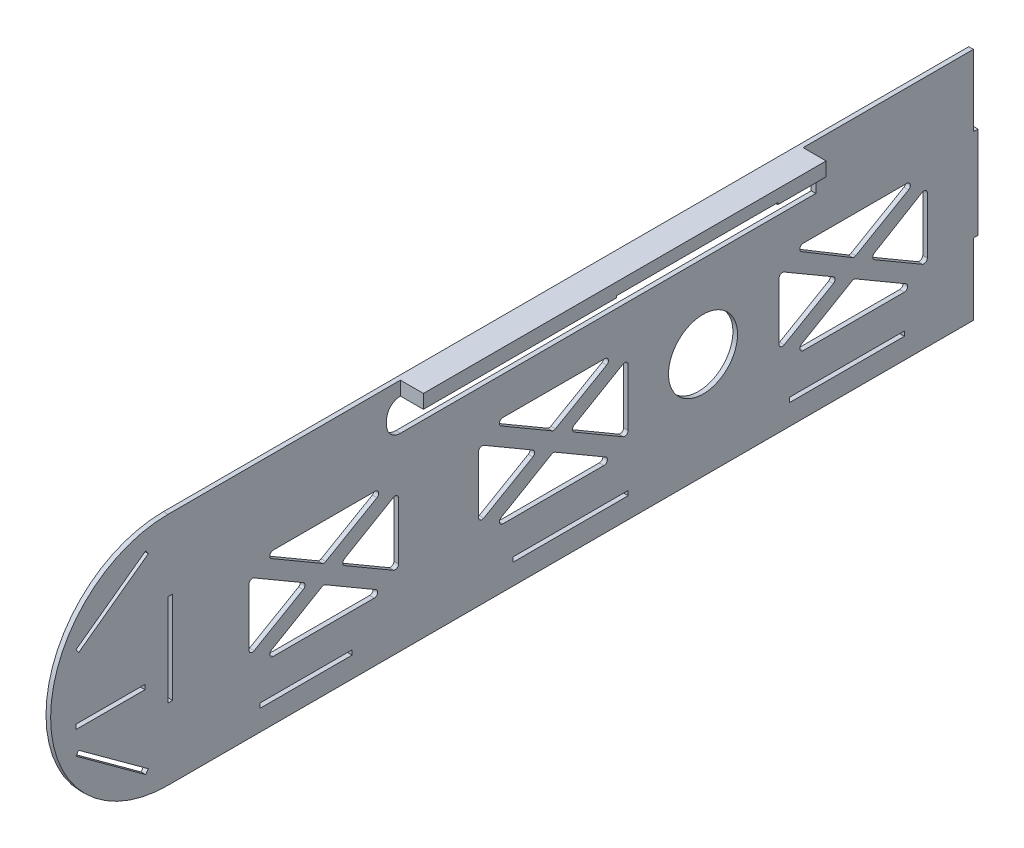
SolidWorks part; units mm, degrees
ref_plane "前视基准面" through (0, 0, 0) normal (0, 0, 1) x (1, 0, 0)
ref_plane "上视基准面" through (0, 0, 0) normal (0, 1, 0) x (1, 0, 0)
ref_plane "右视基准面" through (0, 0, 0) normal (1, 0, 0) x (0, 0, -1)
sketch "草图1" plane through (0, 0, 0) normal (1, 0, 0) x (0, 0, -1)
  line L0 (95, 39) -> (95, 37)
  line L1 (0, 51) -> (139, 51)
  line L2 (0, 51) -> (0, -51)
  line L3 (0, -51) -> (350, -51)
  line L4 (350, 51) -> (350, -51)
  line L5 (145, 51) -> (281.5, 51)
  line L6 (101, 31) -> (275.5, 31)
  line L7 (281.5, 39) -> (281.5, 36)
  line L8 (337.5, 51) -> (350, 51)
  line L10 (-40, -10) -> (-10, -10)
  line L11 (-40, -10) -> (-40, -8)
  line L12 (-40, -8) -> (-10, -8)
  line L13 (-10, -10) -> (-10, -8)
  line L22 (145.5484, 14.6595) -> (189.8851, 14.6595)
  line L23 (135, 7.0479) -> (135, -17.7392)
  line L24 (145.5484, -25.3405) -> (189.4516, -25.3405)
  line L25 (200, 7.3884) -> (200, -17.3884)
  line L29 (176.5069, -6.2957) -> (197.7442, -18.6841)
  line L30 (158.585, -4.0984) -> (137.2558, 8.3436)
  line L31 (137.2514, -19.0374) -> (158.5806, -6.6923)
  line L32 (176.5069, -3.7043) -> (197.7442, 8.6841)
  line L33 (144.7926, 11.8638) -> (166.8743, -1.0172)
  line L34 (190.6365, 11.8613) -> (168.3815, -1.0197)
  line L35 (168.2558, -9.7397) -> (190.2074, -22.5448)
  line L36 (144.7926, -22.5448) -> (166.7442, -9.7397)
  line L37 (276.0709, 15) -> (321.089, 15)
  line L38 (265.5225, 6.9941) -> (265.5225, -17.793)
  line L39 (276.0709, -25.3943) -> (319.9742, -25.3943)
  line L40 (330, 6.9941) -> (330, -17.478)
  line L41 (307.0294, -6.69) -> (327.7442, -18.7736)
  line L42 (289.1076, -4.1523) -> (267.7784, 8.2898)
  line L43 (267.7739, -19.0912) -> (289.1032, -6.7462)
  line L44 (307.0153, -4.107) -> (327.7301, 8.2815)
  line L45 (275.2981, 12.2144) -> (297.3797, -1.0609)
  line L46 (321.8404, 12.2018) -> (298.904, -1.0735)
  line L47 (298.7784, -9.7935) -> (320.73, -22.5987)
  line L48 (275.3151, -22.5987) -> (297.2667, -9.7935)
  line L49 (-40, 20) -> (-9.6982, 42.0918)
  line L50 (-40, 20) -> (-38.8218, 18.3839)
  line L51 (-9.6982, 42.0918) -> (-8.5199, 40.4757)
  line L52 (-38.8218, 18.3839) -> (-8.5199, 40.4757)
  line L53 (-51, 0) -> (0, 0)
  line L54 (-38.8218, -18.3839) -> (-8.5199, -40.4757)
  line L55 (-9.6982, -42.0918) -> (-8.5199, -40.4757)
  line L56 (-40, -20) -> (-38.8218, -18.3839)
  line L57 (-40, -20) -> (-9.6982, -42.0918)
  line L58 (40, -40) -> (80, -40)
  line L59 (40, -40) -> (40, -42)
  line L60 (80, -40) -> (80, -42)
  line L61 (40, -42) -> (80, -42)
  line L62 (150, -40) -> (200, -40)
  line L63 (150, -40) -> (150, -42)
  line L64 (200, -40) -> (200, -42)
  line L65 (150, -42) -> (200, -42)
  line L66 (270, -40) -> (320, -40)
  line L67 (270, -40) -> (270, -42)
  line L68 (320, -40) -> (320, -42)
  line L69 (270, -42) -> (320, -42)
  line L70 (350, 20) -> (352, 20)
  line L71 (350, 20) -> (350, -20)
  line L72 (352, 20) -> (352, -20)
  line L73 (350, -20) -> (352, -20)
  line L74 (0, 20) -> (0, -20)
  line L75 (0, 20) -> (2, 20)
  line L76 (0, -20) -> (2, -20)
  line L77 (2, 20) -> (2, -20)
  line L78 (139, 51) -> (145, 51)
  line L79 (281.5, 51) -> (337.5, 51)
  line L80 (101, 45) -> (275.5, 45)
  line L81 (101, 31) -> (101, 45)
  line L82 (281.5, 36) -> (281.5, 31)
  line L83 (45.7401, 14.6595) -> (90.0769, 14.6595)
  line L84 (35.1917, 7.0479) -> (35.1917, -17.7392)
  line L85 (275.5, 31) -> (281.5, 31)
  line L86 (45.7401, -25.3405) -> (89.6434, -25.3405)
  line L87 (185, 45) -> (255, 45)
  line L88 (185, 45) -> (185, 45.8)
  line L89 (185, 45.8) -> (255, 45.8)
  line L90 (255, 45) -> (255, 45.8)
  line L91 (100.1917, 7.0479) -> (100.1917, -17.729)
  line L92 (76.6986, -6.6362) -> (97.9359, -19.0246)
  line L93 (58.7768, -4.0984) -> (37.4476, 8.3436)
  line L94 (37.4431, -19.0374) -> (58.7724, -6.6923)
  line L95 (76.6986, -4.0448) -> (97.9359, 8.3436)
  line L96 (44.9843, 11.8638) -> (67.066, -1.0172)
  line L97 (90.8283, 11.8613) -> (68.5732, -1.0197)
  line L98 (68.4476, -9.7397) -> (90.3992, -22.5448)
  line L99 (44.9843, -22.5448) -> (66.9359, -9.7397)
  arc A0 (0, 51) -> (0, -51) centre (0, 0) ccw
  arc A1 (97.9359, 8.3436) -> (100.1917, 7.0479) centre (98.6917, 7.0479) cw
  arc A3 (101, 31) -> (95, 37) centre (101, 37) cw
  arc A4 (100.1917, -17.729) -> (97.9359, -19.0246) centre (98.6917, -17.729) cw
  arc A17 (197.7442, 8.6841) -> (200, 7.3884) centre (198.5, 7.3884) cw
  arc A18 (200, -17.3884) -> (197.7442, -18.6841) centre (198.5, -17.3884) cw
  arc A19 (176.5069, -6.2957) -> (176.5069, -3.7043) centre (177.2627, -5) cw
  arc A20 (158.585, -4.0984) -> (158.5806, -6.6923) centre (157.8292, -5.3941) cw
  arc A21 (137.2514, -19.0374) -> (135, -17.7392) centre (136.5, -17.7392) cw
  arc A22 (135, 7.0479) -> (137.2558, 8.3436) centre (136.5, 7.0479) cw
  arc A23 (144.7926, -22.5448) -> (145.5484, -25.3405) centre (145.5484, -23.8405) ccw
  arc A24 (189.4516, -25.3405) -> (190.2074, -22.5448) centre (189.4516, -23.8405) ccw
  arc A25 (168.2558, -9.7397) -> (166.7442, -9.7397) centre (167.5, -11.0354) ccw
  arc A26 (144.7926, 11.8638) -> (145.5484, 14.6595) centre (145.5484, 13.1595) cw
  arc A27 (189.8851, 14.6595) -> (190.6365, 11.8613) centre (189.8851, 13.1595) cw
  arc A28 (168.3815, -1.0197) -> (166.8743, -1.0172) centre (167.6301, 0.2785) cw
  arc A29 (327.7301, 8.2815) -> (330, 6.9941) centre (328.5, 6.9941) cw
  arc A30 (330, -17.478) -> (327.7442, -18.7736) centre (328.5, -17.478) cw
  arc A31 (307.0294, -6.69) -> (307.0153, -4.107) centre (307.7852, -5.3943) cw
  arc A32 (289.1076, -4.1523) -> (289.1032, -6.7462) centre (288.3518, -5.4479) cw
  arc A33 (267.7739, -19.0912) -> (265.5225, -17.793) centre (267.0225, -17.793) cw
  arc A34 (265.5225, 6.9941) -> (267.7784, 8.2898) centre (267.0225, 6.9941) cw
  arc A35 (275.3151, -22.5987) -> (276.0709, -25.3943) centre (276.0709, -23.8943) ccw
  arc A36 (319.9742, -25.3943) -> (320.73, -22.5987) centre (319.9742, -23.8943) ccw
  arc A37 (298.7784, -9.7935) -> (297.2667, -9.7935) centre (298.0225, -11.0892) ccw
  arc A38 (275.2981, 12.2144) -> (276.0709, 15) centre (276.0709, 13.5) cw
  arc A39 (321.089, 15) -> (321.8404, 12.2018) centre (321.089, 13.5) cw
  arc A40 (298.904, -1.0735) -> (297.3797, -1.0609) centre (298.1526, 0.2247) cw
  circle A41 centre (232.5, -5) radius 15
  arc A43 (76.6986, -6.6362) -> (76.6986, -4.0448) centre (77.4544, -5.3405) cw
  arc A44 (281.5, 39) -> (275.5, 45) centre (275.5, 39) ccw
  arc A45 (101, 45) -> (95, 39) centre (101, 39) ccw
  arc A46 (58.7768, -4.0984) -> (58.7724, -6.6923) centre (58.021, -5.3941) cw
  arc A47 (37.4431, -19.0374) -> (35.1917, -17.7392) centre (36.6917, -17.7392) cw
  arc A48 (35.1917, 7.0479) -> (37.4476, 8.3436) centre (36.6917, 7.0479) cw
  arc A49 (44.9843, -22.5448) -> (45.7401, -25.3405) centre (45.7401, -23.8405) ccw
  arc A50 (89.6434, -25.3405) -> (90.3992, -22.5448) centre (89.6434, -23.8405) ccw
  arc A51 (68.4476, -9.7397) -> (66.9359, -9.7397) centre (67.6917, -11.0354) ccw
  arc A52 (44.9843, 11.8638) -> (45.7401, 14.6595) centre (45.7401, 13.1595) cw
  arc A53 (90.0769, 14.6595) -> (90.8283, 11.8613) centre (90.0769, 13.1595) cw
  arc A54 (68.5732, -1.0197) -> (67.066, -1.0172) centre (67.8218, 0.2785) cw
  point P5 (40.1917, 14.6595)
  point P7 (281.5, 31)
  point P8 (286.5, 50)
  point P21 (95, 31)
  point P24 (95.6629, 14.6595)
  point P28 (40.1917, -25.3405)
  point P29 (95.1917, -25.3405)
  point P30 (40.1917, -25.3405)
  point P31 (35.1917, -20.3405)
  point P32 (100, 30)
  point P33 (100.1917, -20.3405)
  point P34 (100.1917, 9.6595)
  point P35 (35.1917, 9.6595)
  point P53 (140, 14.6595)
  point P58 (195.4712, 14.6595)
  point P59 (140, -25.3405)
  point P60 (195, -25.3405)
  point P61 (140, -25.3405)
  point P62 (135, -20.3405)
  point P63 (200, -20)
  point P64 (200, 10)
  point P65 (135, 9.6595)
  point P124 (270.5225, 15)
  point P129 (325.9937, 15)
  point P130 (270.5225, -25.3943)
  point P131 (325.5225, -25.3943)
  point P132 (270.5225, -25.3943)
  point P133 (265.5225, -20.3943)
  point P134 (330, -20.3943)
  point P135 (330, 9.6057)
  point P136 (265.5225, 9.6057)
  point P169 (350, -20)
  point P182 (-9.6982, -42.0918)
  point P184 (-40, -20)
  point P189 (352, 20)
  point P190 (352, -20)
  point P198 (350, 20)
  dimension "D5" = 1.5
  dimension "D6" = 1.5
  dimension "D7" = 1.5
  dimension "D8" = 1.5
  dimension "D9" = 1.5
  dimension "D10" = 1.5
  dimension "D11" = 1.5
  dimension "D12" = 1.5
  dimension "D13" = 1.5
  dimension "D14" = 1.5
  dimension "D15" = 1.5
  dimension "D16" = 1.5
  dimension "D17" = 1.5
  dimension "D18" = 1.5
  dimension "D19" = 1.5
  dimension "D20" = 1.5
  dimension "D21" = 1.5
  dimension "D22" = 1.5
  dimension "D23" = 1.5
  dimension "D24" = 1.5
  dimension "D25" = 1.5
  dimension "D26" = 1.5
  dimension "D27" = 1.5
  dimension "D28" = 1.5
  dimension "D29" = 1.5
  dimension "D30" = 1.5
  dimension "D31" = 1.5
  dimension "D32" = 1.5
  dimension "D33" = 1.5
  dimension "D34" = 1.5
  dimension "D35" = 1.5
  dimension "D36" = 1.5
  dimension "D37" = 1.5
  dimension "D38" = 1.5
  dimension "D39" = 1.5
  dimension "D40" = 1.5
  dimension "D41" = 2
  dimension "D42" = 37.5
  dimension "D43" = 2
extrude "凸台-拉伸3" add sketch "草图1" along normal blind 2 contours L79 L5 L78 L1 L2 L75 L77 L76 L3 L4 L8 A51 L98 A50 L86 A49 L99 A45 L80 L88 L89 L90 A44 L7 L82 L85 L6 A3 L0 A41 A37 L47 A36 L39 A35 L48 A25 L35 A24 L24 A23 L36 | L2 A0 L53 L52 L50 L49 L51 | L53 A0 L2 L57 L56 L54 L55 L13 L10 L11 L12 | L70 L71 L73 L72
sketch "草图2" plane through (0, 0, 0) normal (1, 0, 0) x (0, 0, -1)
  line L31 (101, 45) -> (101, 51)
  line L32 (101, 45) -> (276, 45)
  line L33 (101, 51) -> (276, 51)
  line L34 (276, 45) -> (276, 51)
  line L35 (0, 51) -> (350, 51) construction
  line L36 (185, 45) -> (185, 45.8)
  line L37 (185, 45) -> (255, 45)
  line L38 (185, 45.8) -> (255, 45.8)
  line L39 (255, 45) -> (255, 45.8)
extrude "凸台-拉伸4" add sketch "草图2" along normal blind 12
